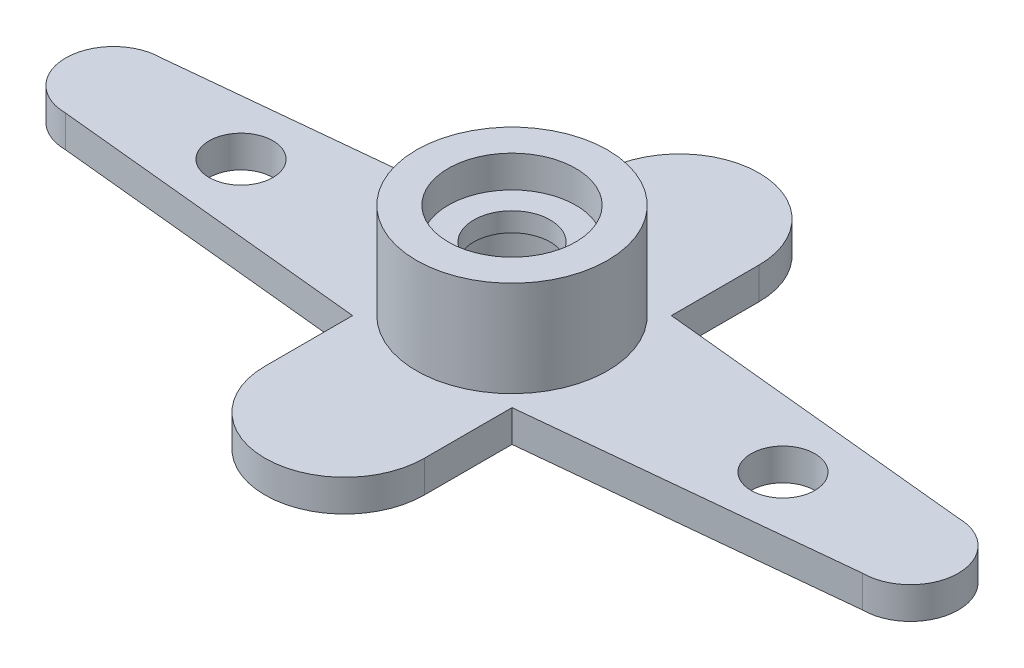
SolidWorks part; units mm, degrees
material "Plain Carbon Steel"
ref_plane "Front Plane" through (0, 0, 0) normal (0, 0, 1) x (1, 0, 0)
ref_plane "Top Plane" through (0, 0, 0) normal (0, 1, 0) x (1, 0, 0)
ref_plane "Right Plane" through (0, 0, 0) normal (1, 0, 0) x (0, 0, -1)
sketch "Sketch1" plane through (0, 0, 0) normal (0, 1, 0) x (1, 0, 0)
  line L0 (0, 82.722) -> (0, -84.0509) construction
  line L1 (-29.5673, 0) -> (39.866, 0) construction
  line L2 (-12.5, 12.5) -> (12.5, 12.5) construction
  line L3 (12.5, 12.5) -> (12.5, 26.25)
  line L4 (12.5, 26.25) -> (-12.5, 26.25) construction
  line L5 (-12.5, 26.25) -> (-12.5, 12.5)
  line L6 (12.5, -26.25) -> (-12.5, -26.25) construction
  line L7 (-12.5, -12.5) -> (12.5, -12.5) construction
  line L8 (-12.5, -26.25) -> (-12.5, -12.5)
  line L9 (12.5, -12.5) -> (12.5, -26.25)
  line L10 (-62.5, -7.5) -> (-62.5, 7.5) construction
  line L11 (-12.5, 12.5) -> (-62.5, 7.5)
  line L12 (-62.5, -7.5) -> (-12.5, -12.5)
  line L13 (62.5, 7.5) -> (62.5, -7.5) construction
  line L14 (12.5, 12.5) -> (62.5, 7.5)
  line L15 (62.5, -7.5) -> (12.5, -12.5)
  circle A0 centre (0, 0) radius 10
  arc A1 (12.5, 26.25) -> (-12.5, 26.25) centre (0, 26.25) ccw
  arc A2 (-12.5, -26.25) -> (12.5, -26.25) centre (0, -26.25) ccw
  arc A3 (-62.5, -7.5) -> (-62.5, 7.5) centre (-62.5, 0) cw
  arc A4 (62.5, 7.5) -> (62.5, -7.5) centre (62.5, 0) cw
  point P7 (12.5, 19.375)
  point P10 (0, 12.5)
  point P18 (0, -12.5)
  point P23 (-62.5, 0)
  point P28 (62.5, 0)
  dimension "D1" = 20
  dimension "D2" = 12.5
  dimension "D3" = 25
  dimension "D4" = 26.25
  dimension "D5" = 15
  dimension "D6" = 62.5
  dimension "D7" = 62.5
extrude "Boss-Extrude1" add sketch "Sketch1" along normal mid plane 5
sketch "Sketch2" plane through (0, 2.5, 0) normal (0, 1, 0) x (1, 0, 0)
  circle A0 centre (0, 0) radius 15
  circle A3 centre (0, 0) radius 10
  dimension "D1" = 30
  dimension "D2" = 20
extrude "Boss-Extrude2" add sketch "Sketch2" along normal blind 15
sketch "Sketch3" plane through (0, 2.5, 0) normal (0, 1, 0) x (1, 0, 0)
  line L0 (-79.2105, 0) -> (78.9841, 0) construction
  line L1 (0, 52.4138) -> (0, -71.009) construction
  circle A0 centre (42.5, 0) radius 5
  circle A1 centre (-42.5, 0) radius 5
  dimension "D1" = 10
  dimension "D2" = 85
extrude "Cut-Extrude1" cut sketch "Sketch3" against normal through all
sketch "Sketch4" plane through (0, 0, 0) normal (0, 1, 0) x (1, 0, 0)
  circle A0 centre (0, 0) radius 10
  circle A1 centre (0, 0) radius 10 construction
  circle A2 centre (0, 0) radius 6
  dimension "D1" = 12
extrude "Boss-Extrude3" add sketch "Sketch4" along normal blind 3 from offset 9.5
